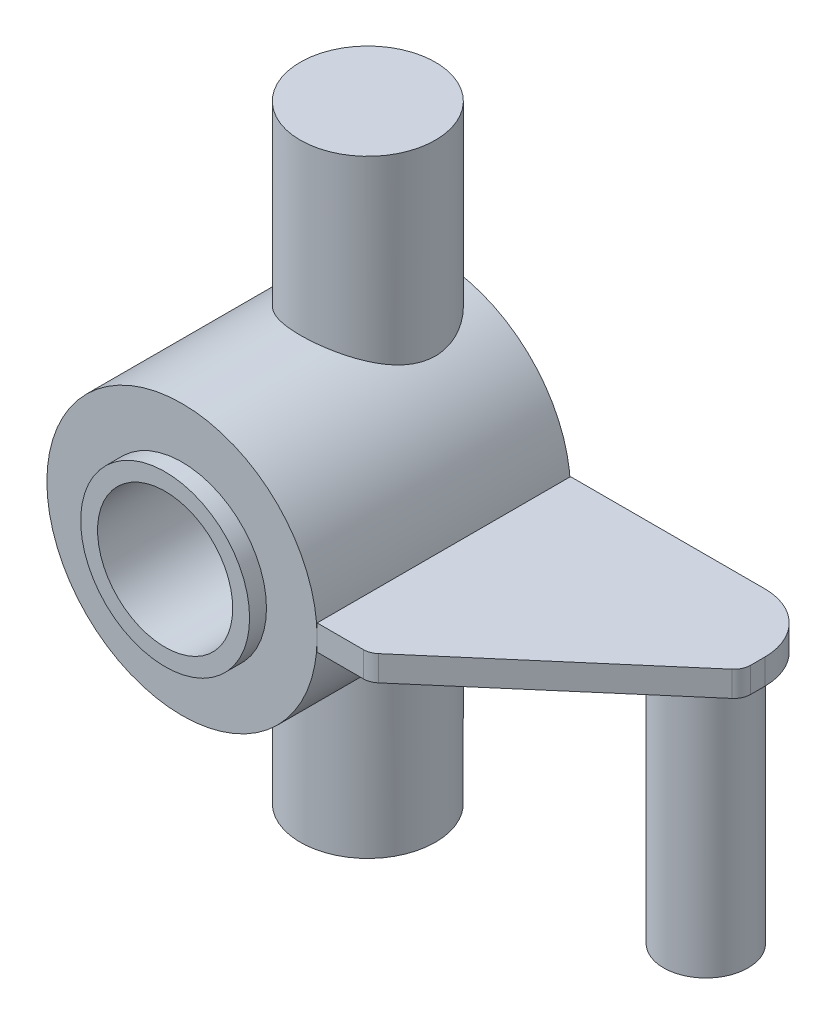
SolidWorks part; units mm, degrees
ref_plane "Front Plane" through (0, 0, 0) normal (0, 0, 1) x (1, 0, 0)
ref_plane "Top Plane" through (0, 0, 0) normal (0, 1, 0) x (1, 0, 0)
ref_plane "Right Plane" through (0, 0, 0) normal (1, 0, 0) x (0, 0, -1)
sketch "Sketch1" plane through (0, 0, 0) normal (0, 0, 1) x (1, 0, 0)
  line L0 (8.8, 8) -> (-8.8, 8) construction
  line L1 (8.8, 0) -> (-8.8, 0) construction
  circle A0 centre (0, 0) radius 8
  dimension "D1" = 16
extrude "Boss-Extrude1" add sketch "Sketch1" along normal blind 15
sketch "Sketch2" plane through (0, 0, 15) normal (0, 0, 1) x (1, 0, 0)
  circle A0 centre (0, 0) radius 5
  circle A1 centre (0, 0) radius 4
  dimension "D1" = 10
  dimension "D2" = 8
extrude "Boss-Extrude2" add sketch "Sketch2" along normal blind 1 contours A0
sketch "Sketch3" plane through (0, 0, 15) normal (0, 0, 1) x (1, 0, 0)
  circle A1 centre (0, 0) radius 4
  circle A2 centre (0, 0) radius 4
  dimension "D1" = 0
extrude "Cut-Extrude1" cut sketch "Sketch3" against normal blind 15
ref_plane "Plane1" through (0, 8, 0) normal (0, 1, 0) x (1, 0, 0)
sketch "Sketch4" plane through (0, 8, 0) normal (0, 1, 0) x (1, 0, 0)
  circle A5 centre (0, -4) radius 4
  dimension "D1" = 8
  dimension "D2" = 4
extrude "Boss-Extrude3" add sketch "Sketch4" along normal blind 10 and the other way up to surface separate body other way up to face at (8, 0, 15)
ref_plane "Plane2" through (0, -8, 0) normal (0, -1, 0) x (-1, 0, 0)
sketch "Sketch6" plane through (0, -8, 0) normal (0, -1, 0) x (-1, 0, 0)
  circle A0 centre (0, -4) radius 4
  dimension "D1" = 4
  dimension "D2" = 8
extrude "Boss-Extrude4" add sketch "Sketch6" along normal blind 10 and the other way up to surface other way up to face at (8, 0, 15)
ref_plane "Plane3" through (8, 0, 0) normal (1, 0, 0) x (0, 0, -1)
sketch "Sketch7" plane through (8, 0, 0) normal (1, 0, 0) x (0, 0, -1)
  line L9 (0, -0.75) -> (-15, -0.75)
  line L10 (0, -0.75) -> (0, 0.75)
  line L11 (0, 0.75) -> (-15, 0.75)
  line L12 (-15, -0.75) -> (-15, 0.75)
  point P4 (0, 0)
  dimension "D1" = 15
  dimension "D2" = 1.5
extrude "Boss-Extrude5" add sketch "Sketch7" along normal blind 15 separate body
sketch "Sketch9" plane through (0, -0.75, 0) normal (0, -1, 0) x (1, 0, 0)
  line L4 (8, 15) -> (8, 0)
  line L5 (8, 0) -> (23, 0)
  line L6 (23, 0) -> (23, 15)
  line L7 (23, 15) -> (8, 15)
  line L8 (8, 15) -> (8, 0)
  line L9 (8, 0) -> (23, 0)
  line L10 (23, 0) -> (23, 15)
  line L11 (23, 15) -> (8, 15)
  circle A0 centre (19.5, 3.5) radius 3.5
  line M8 (23, 0) -> (23, 15)
  dimension "D1" = 0
  dimension "D2" = 7
extrude "Cut-Extrude2" cut sketch "Sketch9" against normal blind 15 contours A0 L9 M8
sketch "Sketch11" plane through (0, -0.75, 0) normal (0, -1, 0) x (-1, 0, 0)
  line L0 (-11.1081, -15) -> (-23, -4.7928) construction
  line L1 (-23, -15) -> (-8, -15) construction
  line L2 (-23, -15) -> (-23, -3.5) construction
  line M3 (-23, -3.5) -> (-23, -15)
  line M4 (-23, -15) -> (-8, -15)
extrude "Cut-Extrude3" cut sketch "Sketch11" against normal blind 15 contours L0 M4 M3
fillet "Fillet1" radius 1 1 edges at (11.1081, 0, 15)
fillet "Fillet2" radius 1 1 edges at (23, 0, 4.7928)
sketch "Sketch12" plane through (0, -0.75, 0) normal (0, -1, 0) x (1, 0, 0)
  arc A2 (19.5, 0) -> (23, 3.5) centre (19.5, 3.5) ccw construction
  arc A3 (19.5, 0) -> (23, 3.5) centre (19.5, 3.5) ccw
  circle A4 centre (19.4463, 3.435) radius 2.5
  point P1 (21.9749, 1.0251)
  dimension "D1" = 5
  dimension "D3" = 2.5286
  dimension "D2" = 3.435
extrude "Boss-Extrude6" add sketch "Sketch12" along normal blind 15 contours A4
